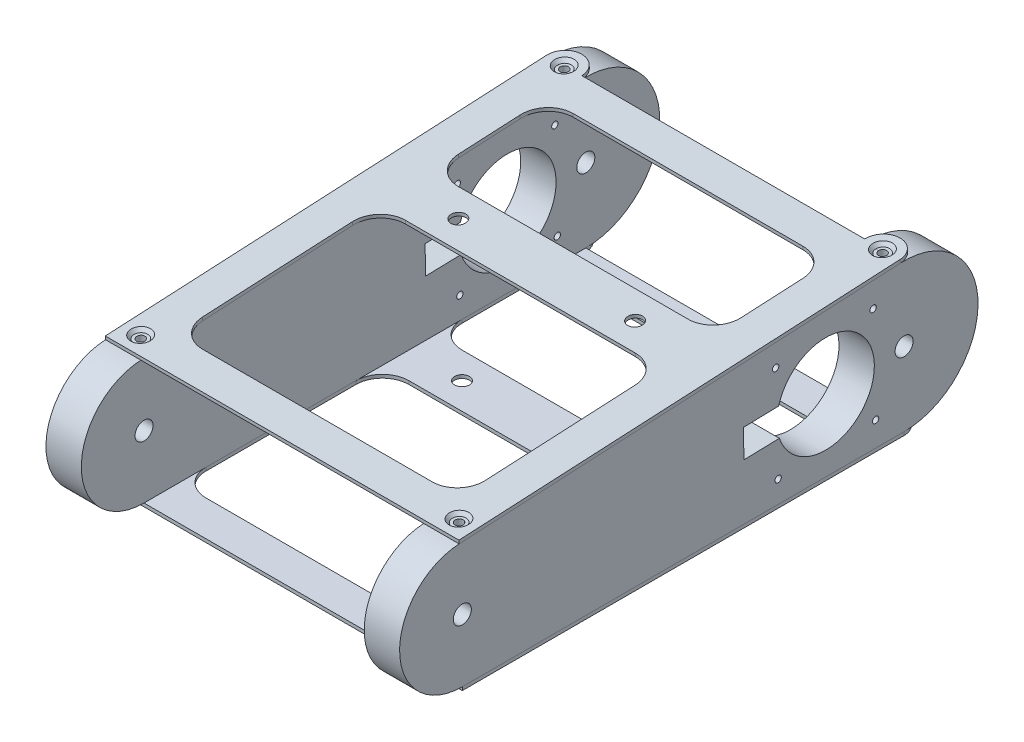
SolidWorks part; units mm, degrees
ref_plane "Front Plane" through (0, 0, 0) normal (0, 0, 1) x (1, 0, 0)
ref_plane "Top Plane" through (0, 0, 0) normal (0, 1, 0) x (1, 0, 0)
ref_plane "Right Plane" through (0, 0, 0) normal (1, 0, 0) x (0, 0, -1)
ref_plane "Plane1" through (50.8, 0, 0) normal (1, 0, 0) x (0, 0, -1)
sketch "Sketch1" plane through (50.8, 0, 0) normal (1, 0, 0) x (0, 0, -1)
  line L0 (-158.647, -4.0425) -> (-1.5131, -0.0386) construction
  line L1 (-159.4706, 12.1066) -> (-1.0294, 20.1864) construction
  line L2 (-158.647, -20.2127) -> (0, -20.2127) construction
  line L3 (-159.794, 18.4484) -> (-1.3528, 26.5282)
  line L4 (-158.647, -26.5627) -> (0, -26.5627)
  circle A0 centre (0, 0) radius 29.845 construction
  circle A1 centre (-158.647, -4.0425) radius 23.622 construction
  arc A2 (-159.4706, 12.1066) -> (-158.647, -20.2127) centre (-158.647, -4.0425) ccw construction
  arc A3 (0, -20.2127) -> (-1.0294, 20.1864) centre (0, 0) ccw construction
  arc A4 (0, -26.5627) -> (-1.3528, 26.5282) centre (0, 0) ccw
  arc A5 (-159.794, 18.4484) -> (-158.647, -26.5627) centre (-158.647, -4.0425) ccw
  circle A6 centre (-158.647, -4.0425) radius 3.2385
  circle A7 centre (0, 0) radius 3.2385
  dimension "D1" = 59.69
  dimension "D2" = 47.244
  dimension "D3" = 40.4254
  dimension "D4" = 32.3403
  dimension "D8" = 6.477
  dimension "D6" = 157.1849
  dimension "D7" = 6.35
extrude "Boss-Extrude1" add sketch "Sketch1" along normal blind 12.7
sketch "Sketch2" plane through (63.5, 0, 0) normal (1, 0, 0) x (0, 0, -1)
  line L0 (-158.647, -4.0425) -> (0, 0) construction
  line L2 (-44.7801, -6.2244) -> (-57.4801, -6.548)
  line L3 (-45.0389, 3.9356) -> (-57.7389, 3.612)
  line L4 (-57.4801, -6.548) -> (-57.7389, 3.612)
  circle A0 centre (0, 0) radius 23.8125 construction
  circle A1 centre (-28.169, -0.7178) radius 4.3656 construction
  arc A2 (-44.7801, -6.2244) -> (-45.0389, 3.9356) centre (-28.169, -0.7178) ccw
  point P5 (-41.7318, 3.7539)
  point P11 (-53.8636, 4.6245)
  dimension "D1" = 8.7312
  dimension "D2" = 47.625
  dimension "D3" = 35
  dimension "D4" = 10.16
  dimension "D5" = 12.7
extrude "Cut-Extrude1" cut sketch "Sketch2" against normal up to surface (12.7 mm away) up to face at (50.8, -2.0035, 78.6257)
sketch "Sketch5" plane through (63.5, 0, 0) normal (1, 0, 0) x (0, 0, -1)
  line L0 (0, 0) -> (-158.647, -4.0425) construction
  line L1 (-46.1091, 16.3308) -> (-11.1204, 17.2223) construction
  line L2 (-46.1091, 16.3308) -> (-45.2175, -18.6579) construction
  line L3 (-11.1204, 17.2223) -> (-10.2289, -17.7663) construction
  line L4 (-45.2175, -18.6579) -> (-10.2289, -17.7663) construction
  arc A0 (-44.7801, -6.2244) -> (-45.0389, 3.9356) centre (-28.169, -0.7178) ccw construction
  circle A1 centre (-46.1091, 16.3308) radius 1.143
  circle A2 centre (-11.1204, 17.2223) radius 1.143
  circle A3 centre (-10.2289, -17.7663) radius 1.143
  circle A4 centre (-45.2175, -18.6579) radius 1.143
  dimension "D1" = 2.286
extrude "Cut-Extrude3" cut sketch "Sketch5" against normal up to surface (12.7 mm away) up to face at (50.8, -1.0881, 42.7008)
mirror "Mirror2" about plane through (0, 0, 0) normal (1, 0, 0) of bodies 105 102
sketch "Sketch6" plane through (0, 26.5282, 1.3528) normal (0, 0.9987, 0.0509) x (1, 0, 0)
  line L0 (-50.8, 0) -> (50.8, 0)
  line L2 (-63.5, 0) -> (-63.5, -158.647)
  line L3 (-63.5, -158.647) -> (63.5, -158.647)
  line L4 (63.5, 0) -> (63.5, -158.647)
  arc A1 (-63.5, 0) -> (-50.8, 0) centre (-57.15, 0) cw
  arc A2 (50.8, 0) -> (63.5, 0) centre (57.15, 0) cw
extrude "Boss-Extrude2" add sketch "Sketch6" along normal blind 1.2 separate body
hole_wizard "CSK for #6 Flat Head Machine Screw1" positions "Sketch7" profile "Sketch8" countersink size "#6" standard "ANSI Inch" end condition up to next
sketch "Sketch7" plane through (0, 27.7266, 1.4139) normal (0, 0.9987, 0.0509) x (1, 0, 0)
  line L0 (-63.5, 0) -> (-50.8, 0) construction
  line L1 (63.5, 0) -> (50.8, 0) construction
  line L2 (-63.5, 0) -> (-63.5, -158.647) construction
  line L3 (-63.5, -158.647) -> (63.5, -158.647) construction
  circle A0 centre (-57.15, -152.297) radius 6.35 construction
  point P0 (-57.15, 0)
  point P4 (57.15, 0)
  point P8 (-57.15, -152.297)
  point P10 (57.15, -152.297)
  point P22 (0, 0)
sketch "Sketch8" plane through (-57.15, 27.7266, 1.4139) normal (1, 0, 0) x (0, -0.0509, 0.9987)
  line L0 (0, 0) -> (0, 24.5242)
  line L1 (0, 24.5242) -> (2.1526, 24.5242)
  line L2 (2.1526, 24.5242) -> (2.1526, 1.5998)
  line L3 (2.1526, 1.5998) -> (3.5433, 0)
  line L5 (3.5433, 0) -> (0, 0)
  line L6 (-2.1526, 1.5998) -> (-3.5433, 0) construction
  line L11 (0, -6.35) -> (0, 107.95) construction
  dimension "Thru Hole Dia." = 4.3053
  dimension "Thru Hole Depth" = 24.5242
  dimension "Near C'Sink Dia." = 7.0866
  dimension "Near C'Sink Angle" = 82
sketch "Sketch9" plane through (0, 27.7266, 1.4139) normal (0, 0.9987, 0.0509) x (1, 0, 0)
  line L0 (-31.75, -63.5) -> (31.75, -63.5) construction
  line L1 (0, 0) -> (0, -158.647) construction
  line L2 (50.8, 0) -> (-50.8, 0) construction
  line L3 (-63.5, -158.647) -> (63.5, -158.647) construction
  line L4 (-63.5, 0) -> (-63.5, -158.647) construction
  line L5 (-50.8, -12.7) -> (50.8, -12.7)
  line L6 (-50.8, -12.7) -> (-50.8, -53.975)
  line L7 (-50.8, -53.975) -> (50.8, -53.975)
  line L8 (50.8, -12.7) -> (50.8, -53.975)
  line L9 (-50.8, -73.025) -> (50.8, -73.025)
  line L10 (-50.8, -73.025) -> (-50.8, -145.947)
  line L11 (-50.8, -145.947) -> (50.8, -145.947)
  line L12 (50.8, -73.025) -> (50.8, -145.947)
  circle A0 centre (-31.75, -63.5) radius 2.667
  circle A1 centre (31.75, -63.5) radius 2.667
  circle A2 centre (-31.75, -63.5) radius 9.525 construction
  point P10 (0, -63.5)
  point P19 (0, -12.7)
  dimension "D1" = 5.334
  dimension "D5" = 19.05
  dimension "D2" = 63.5
  dimension "D3" = 63.5
  dimension "D4" = 12.7
  dimension "D6" = 12.7
  dimension "D7" = 12.7
extrude "Cut-Extrude4" cut sketch "Sketch9" against normal up to surface (1.2 mm away) up to face at (-57.15, 26.6555, -1.1441)
fillet "Fillet1" radius 9.525 8 edges at (50.8, 24.3785, 55.2883) (-50.8, 24.3785, 55.2883) (50.8, 26.4806, 14.0669) (-50.8, 26.4806, 14.0669) (-50.8, 23.4083, 74.3136) (50.8, 23.4083, 74.3136) (50.8, 19.6944, 147.141) (-50.8, 19.6944, 147.141)
ref_plane "Plane3" through (0, 0, 0) normal (0, 0.9997, 0.0255) x (0, 0.0255, -0.9997)
mirror "Mirror3" about plane through (0, 0, 0) normal (0, 0.9997, 0.0255) of bodies 108
hole_wizard "#32 (0.116) Diameter Hole1" positions "Sketch10" profile "Sketch12" hole size "#32" standard "ANSI Inch"
sketch "Sketch10" plane through (0, 26.5282, 1.3528) normal (0, 0.9987, 0.0509) x (1, 0, 0)
  line L0 (-63.5, 0) -> (-50.8, 0) construction
  line L1 (63.5, 0) -> (50.8, 0) construction
  point P0 (-57.15, 0)
  point P4 (-57.15, -152.297)
  point P7 (57.15, -152.297)
  point P10 (57.15, 0)
sketch "Sketch12" plane through (-57.15, 26.5282, 1.3528) normal (1, 0, 0) x (0, -0.0509, 0.9987)
  line L0 (0, 0) -> (0, 13.5852)
  line L1 (0, 13.5852) -> (1.4732, 12.7)
  line L2 (1.4732, 12.7) -> (1.4732, 0)
  line L5 (1.4732, 0) -> (0, 0)
  line L10 (0, 13.5852) -> (-1.4732, 12.7) construction
  line L11 (0, -6.35) -> (0, 107.95) construction
  dimension "Hole Dia." = 2.9464
  dimension "Hole Depth" = 12.7
  dimension "Drill Angle" = 118
mirror "Mirror4" about plane through (0, 0, 0) normal (0, 0.9997, 0.0255) of "#32 (0.116) Diameter Hole1"
equation "\"D3@Sketch1\"=0.2 * 25 /pi"
equation "\"D4@Sketch1\"=0.2 * 20 / pi"
equation "\"D1@Sketch2\"=11/32"
equation "\"D2@Sketch2\"=60/32"
equation "\"D3@Sketch2\"=35mm"
